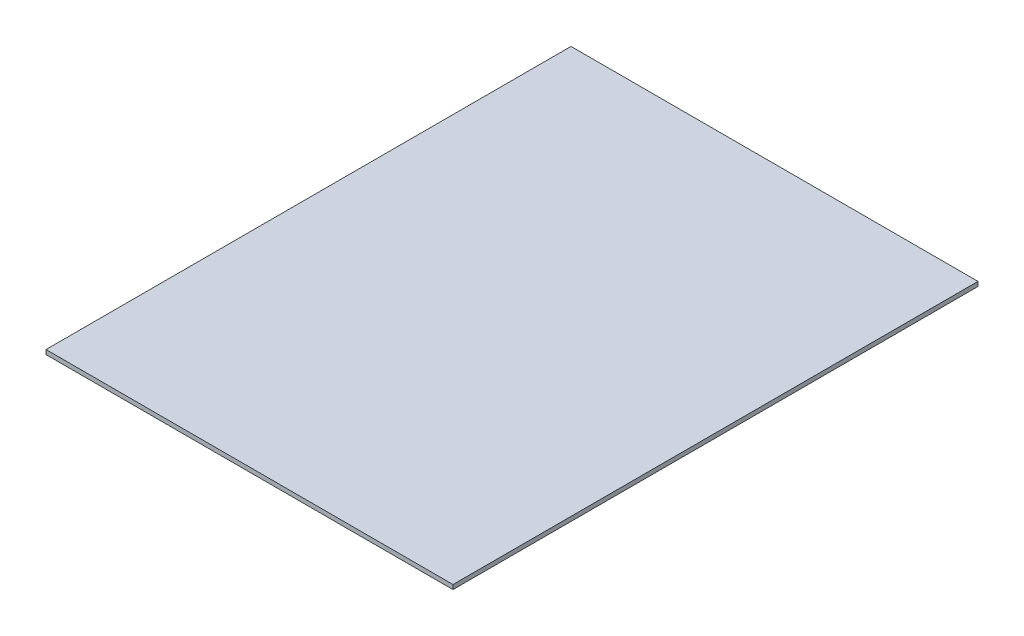
SolidWorks part; units mm, degrees
ref_plane "Front Plane" through (0, 0, 0) normal (0, 0, 1) x (1, 0, 0)
ref_plane "Top Plane" through (0, 0, 0) normal (0, 1, 0) x (1, 0, 0)
ref_plane "Right Plane" through (0, 0, 0) normal (1, 0, 0) x (0, 0, -1)
sketch "Sketch1" plane through (0, 0, 0) normal (0, 1, 0) x (1, 0, 0)
  line L1 (-292.8938, -377.825) -> (292.8937, -377.825)
  line L2 (-292.8938, -377.825) -> (-292.8938, 377.825)
  line L3 (-292.8938, 377.825) -> (292.8937, 377.825)
  line L4 (292.8937, -377.825) -> (292.8937, 377.825)
  line L5 (-292.8938, -377.825) -> (292.8937, 377.825) construction
  line L6 (-292.8938, 377.825) -> (292.8937, -377.825) construction
  point P0 (0, 0)
  dimension "D1" = 755.65
  dimension "D2" = 585.7875
extrude "Boss-Extrude1" add sketch "Sketch1" along normal blind 6.35
